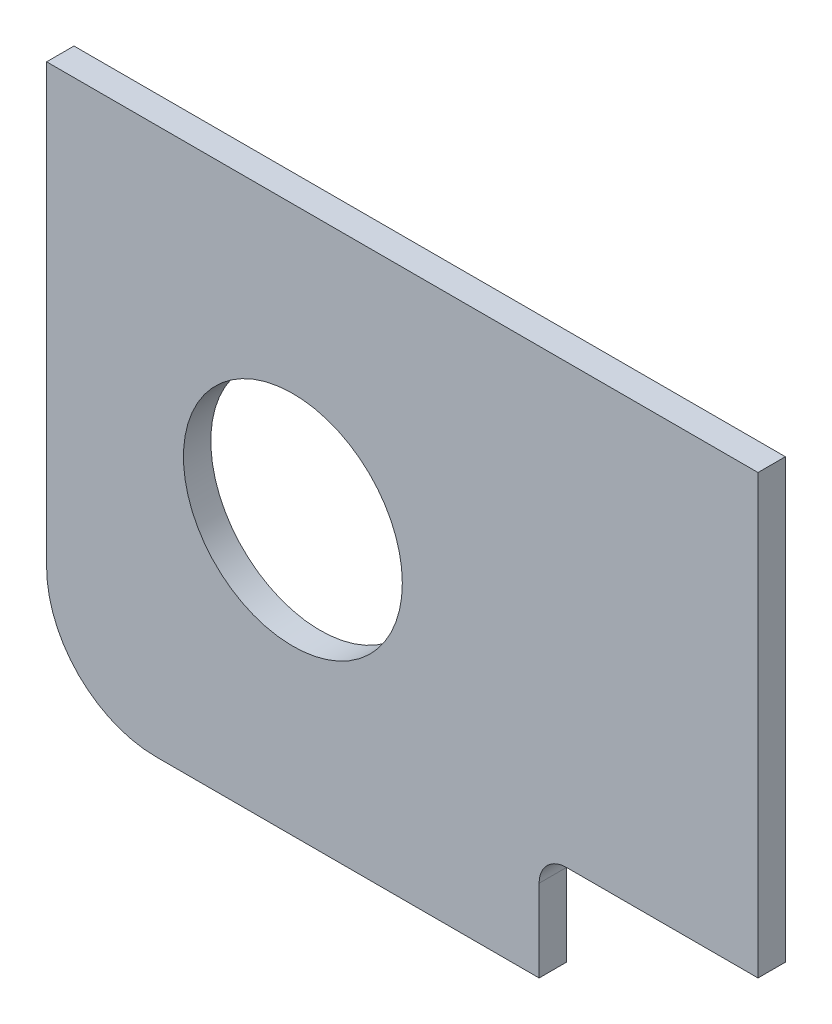
SolidWorks part; units mm, degrees
ref_plane "Ebene vorne" through (0, 0, 0) normal (0, 0, 1) x (1, 0, 0)
ref_plane "Ebene oben" through (0, 0, 0) normal (0, 1, 0) x (1, 0, 0)
ref_plane "Ebene rechts" through (0, 0, 0) normal (1, 0, 0) x (0, 0, -1)
sketch "Skizze1" plane through (0, 0, 0) normal (0, 0, 1) x (1, 0, 0)
  line L0 (20, 0) -> (90, 0)
  line L1 (90, 0) -> (90, 15)
  line L2 (95, 20) -> (130, 20)
  line L3 (130, 20) -> (130, 100)
  line L4 (130, 100) -> (0, 100)
  line L5 (0, 100) -> (0, 20)
  circle A0 centre (45, 50) radius 20
  arc A1 (20, 0) -> (0, 20) centre (20, 20) cw
  arc A2 (95, 20) -> (90, 15) centre (95, 15) ccw
  point P11 (40.272, 100)
  point P12 (20.587, 100)
  point P13 (0, 0)
  point P16 (90, 20)
  dimension "D7" = 40
  dimension "D8" = 20
  dimension "D9" = 5
  dimension "D1" = 130
  dimension "D2" = 100
  dimension "D3" = 40
  dimension "D4" = 20
  dimension "D5" = 45
  dimension "D6" = 50
extrude "Aufsatz-Linear austragen1" add sketch "Skizze1" along normal blind 5
